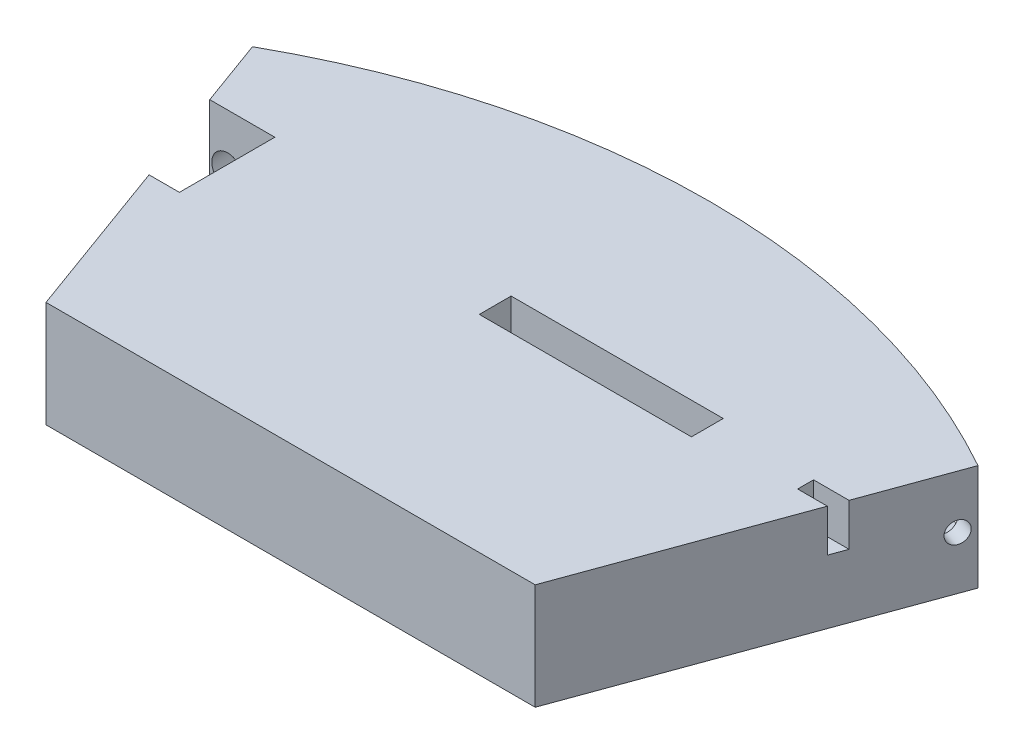
SolidWorks part; units mm, degrees
ref_plane "前视基准面" through (0, 0, 0) normal (0, 0, 1) x (1, 0, 0)
ref_plane "上视基准面" through (0, 0, 0) normal (0, 1, 0) x (1, 0, 0)
ref_plane "右视基准面" through (0, 0, 0) normal (1, 0, 0) x (0, 0, -1)
sketch "草图1" plane through (0, 0, 0) normal (0, 1, 0) x (1, 0, 0)
  line L0 (0, -1000) -> (0, 49000) construction
  line L1 (-34.202, 61.0755) -> (-9.3969, -7.0759)
  line L2 (34.202, 61.0755) -> (9.3969, -7.0759)
  circle A0 centre (0, 0) radius 70
  arc A1 (9.3969, -7.0759) -> (-9.3969, -7.0759) centre (0, -3.6557) cw
  circle A2 centre (0, 0) radius 5
  point P8 (0, -32.8937)
extrude "凸台-拉伸1" add sketch "草图1" along normal blind 48 contours A1 L0 A2 A0 L1 | L0 A1 L2 A0 A2
sketch "草图2" plane through (0, 48, 0) normal (0, 1, 0) x (1, 0, 0)
  line L0 (55.0345, 118.3122) -> (20.1256, 80.8771)
  line L1 (34.202, 61.0755) -> (9.3969, -7.0759) construction
  line L2 (36.2406, 125.1526) -> (55.0345, 118.3122)
  line L3 (36.2406, 125.1526) -> (5.4588, 40.5803)
  line L4 (5.4588, 40.5803) -> (24.2526, 33.7399)
  line L5 (55.0345, 118.3122) -> (24.2526, 33.7399)
  line L6 (36.2406, 125.1526) -> (24.2526, 33.7399) construction
  line L7 (5.4588, 40.5803) -> (55.0345, 118.3122) construction
  point P1 (30.2466, 79.4462)
  point P8 (-0.9024, -2.4793)
  dimension "D1" = 20
  dimension "D2" = 130
  dimension "D3" = 23
  dimension "D4" = 40
sketch "草图3" plane through (0, 0, 0) normal (0, 0, 1) x (1, 0, 0)
  line L0 (34.202, 48) -> (34.202, 0) construction
  line L1 (-34.202, 0) -> (-9.3969, 0) construction
  line L2 (-26.202, 8) -> (32.202, 8)
  line L3 (-26.202, 8) -> (-26.202, 2)
  line L4 (-26.202, 2) -> (32.202, 2)
  line L5 (32.202, 8) -> (32.202, 2)
  line L6 (-26.202, 8) -> (32.202, 2) construction
  line L7 (-26.202, 2) -> (32.202, 8) construction
  line L8 (-34.202, 48) -> (-34.202, 0) construction
  point P1 (3, 5)
  dimension "D1" = 2
  dimension "D2" = 8
  dimension "D3" = 6
  dimension "D4" = 2
extrude "切除-拉伸2" cut sketch "草图3" along normal blind 3 from surface starting at face at (0, 24, -65.5378)
extrude "凸台-拉伸2" add sketch "草图2" against normal blind 13
sketch "草图4" plane through (0, 0, 0) normal (1, 0, 0) x (0, 0, -1)
  line L0 (-13.6557, 48) -> (-13.6557, 0) construction
  line L1 (-13.6557, 48) -> (11.3443, 48)
  line L2 (-13.6557, 48) -> (-13.6557, 10)
  line L3 (-13.6557, 10) -> (11.3443, 10)
  line L4 (11.3443, 48) -> (11.3443, 10)
  line L5 (-13.6557, 48) -> (11.3443, 10) construction
  line L6 (-13.6557, 10) -> (11.3443, 48) construction
  line L8 (70.4669, 35) -> (30.4669, 35)
  line L9 (70.4669, 35) -> (70.4669, 10)
  line L10 (70.4669, 10) -> (30.4669, 10)
  line L11 (30.4669, 35) -> (30.4669, 10)
  line L12 (70.4669, 35) -> (30.4669, 10) construction
  line L13 (70.4669, 10) -> (30.4669, 35) construction
  line L14 (59.1533, 8) -> (67, 8) construction
  line L15 (-13.6557, 0) -> (-7.0759, 0) construction
  line L16 (118.3122, 35) -> (61.0755, 35) construction
  point P4 (-1.1557, 29)
  point P11 (50.4669, 22.5)
  dimension "D1" = 2
  dimension "D2" = 40
  dimension "D3" = 10
  dimension "D5" = 25
extrude "切除-拉伸3" cut sketch "草图4" against normal through all both and the other way through all
chamfer "倒角1" distance 5 angle 45 1 edges at (55.0345, 41.5, -118.3122)
sketch "草图6" plane through (0, 0, 0) normal (0, -1, 0) x (1, 0, 0)
  circle A0 centre (0, 0) radius 6.5
  dimension "D1" = 13
extrude "切除-拉伸4" cut sketch "草图6" against normal blind 2
sketch "草图7" plane through (0, 0, 0) normal (0, 0, 1) x (1, 0, 0)
  line L0 (-1024.202, 5) -> (48975.798, 5) construction
  line L1 (-26.202, 8) -> (-26.202, 2) construction
  line L2 (-34.202, 10) -> (-34.202, 0) construction
  circle A0 centre (-30.202, 5) radius 1.5
  point P5 (-26.202, 5)
  dimension "D1" = 3
  dimension "D2" = 4
extrude "切除-拉伸5" cut sketch "草图7" against normal blind 60
sketch "草图8" plane through (0, 10, 0) normal (0, 1, 0) x (1, 0, 0)
  line L0 (-34.202, 61.0755) -> (-16.1013, 11.3443) construction
  line L1 (-34.7582, 54.7401) -> (-25.7582, 54.7401)
  line L2 (-34.7582, 54.7401) -> (-34.7582, 45.7401)
  line L3 (-34.7582, 45.7401) -> (-25.7582, 45.7401)
  line L4 (-25.7582, 54.7401) -> (-25.7582, 45.7401)
  line L5 (-34.7582, 54.7401) -> (-25.7582, 45.7401) construction
  line L6 (-34.7582, 45.7401) -> (-25.7582, 54.7401) construction
  point P0 (-30.2582, 50.2401)
  dimension "D1" = 9
  dimension "D2" = 9
extrude "切除-拉伸6" cut sketch "草图8" against normal blind 11
sketch "草图10" plane through (10.5718, 0, 3.8478) normal (0.9397, 0, 0.342) x (0.342, 0, -0.9397)
  line L0 (-930.91, 5) -> (49069.09, 5) construction
  line L1 (69.09, 10) -> (69.09, 0) construction
  line L2 (67.59, -995) -> (67.59, 49005) construction
  circle A0 centre (67.59, 5) radius 1
  point P5 (69.09, 5)
  dimension "D1" = 2
  dimension "D2" = 1.5
extrude "切除-拉伸8" cut sketch "草图10" against normal up to surface (1.9464 mm away)
sketch "草图11" plane through (0, 0, -60) normal (0, 0, 1) x (1, 0, 0)
  circle A0 centre (-30.202, 5) radius 0.75
  dimension "D1" = 1.5
extrude "切除-拉伸9" cut sketch "草图11" against normal up to next
sketch "草图12" plane through (0, 10, 0) normal (0, 1, 0) x (1, 0, 0)
  line L1 (-1.653, 52.9115) -> (18.347, 52.9115)
  line L2 (-1.653, 52.9115) -> (-1.653, 49.9115)
  line L3 (-1.653, 49.9115) -> (18.347, 49.9115)
  line L4 (18.347, 52.9115) -> (18.347, 49.9115)
  line L5 (-1.653, 52.9115) -> (18.347, 49.9115) construction
  line L6 (-1.653, 49.9115) -> (18.347, 52.9115) construction
  point P0 (8.347, 51.4115)
  dimension "D1" = 3
  dimension "D2" = 20
  dimension "D3" = 15
extrude "切除-拉伸10" cut sketch "草图12" against normal blind 11
sketch "草图13" plane through (0, 10, 0) normal (0, 1, 0) x (1, 0, 0)
  line L0 (-976.6169, 51.4115) -> (49023.3831, 51.4115) construction
  line L1 (18.347, 49.9115) -> (18.347, 52.9115) construction
  line L3 (27.6086, 52.1615) -> (31.4769, 52.1615)
  line L4 (27.6086, 52.1615) -> (27.6086, 50.6615)
  line L5 (27.6086, 50.6615) -> (31.4769, 50.6615)
  line L6 (31.4769, 52.1615) -> (31.4769, 50.6615)
  line L7 (27.6086, 52.1615) -> (31.4769, 50.6615) construction
  line L8 (27.6086, 50.6615) -> (31.4769, 52.1615) construction
  point P4 (18.347, 51.4115)
  point P5 (29.5428, 51.4115)
  dimension "D1" = 1.5
extrude "切除-拉伸11" cut sketch "草图13" against normal blind 4
sketch "草图14" plane through (0, 48, 0) normal (0, 1, 0) x (1, 0, 0)
  line L0 (51.6245, 114.6554) -> (20.1256, 80.8771) construction
  line L1 (49.7661, 108.2233) -> (49.0348, 108.9053)
  line L2 (49.7661, 108.2233) -> (40.9002, 98.7157)
  line L3 (40.9002, 98.7157) -> (40.1688, 99.3977)
  line L4 (49.0348, 108.9053) -> (40.1688, 99.3977)
  line L5 (49.7661, 108.2233) -> (40.1688, 99.3977) construction
  line L6 (40.9002, 98.7157) -> (49.0348, 108.9053) construction
  line L9 (53.7303, 114.729) -> (16.1013, 11.3443) construction
  point P4 (44.9675, 103.8105)
  dimension "D1" = 1
  dimension "D2" = 13
  dimension "D3" = 13
  dimension "D4" = 1
  dimension "D5" = 90
  dimension "D6" = 4.5
  dimension "D7" = 14
extrude "切除-拉伸12" cut sketch "草图14" against normal up to next
sketch "草图15" plane through (0, 10, 0) normal (0, 1, 0) x (1, 0, 0)
  line L0 (-941.071, 30.4669) -> (49058.929, 30.4669) construction
  line L1 (-51.0427, 30.4669) -> (58.929, 30.4669)
  line L2 (-51.0427, 30.4669) -> (-51.0427, 79.7213)
  line L3 (-51.0427, 79.7213) -> (58.929, 79.7213)
  line L4 (58.929, 30.4669) -> (58.929, 79.7213)
  line L5 (-51.0427, 30.4669) -> (58.929, 79.7213) construction
  line L6 (-51.0427, 79.7213) -> (58.929, 30.4669) construction
  line L7 (-23.0614, 30.4669) -> (23.0614, 30.4669) construction
  point P4 (3.9431, 55.0941)
  point P6 (0, 0)
  point P9 (-51.0427, 33.611)
extrude "切除-拉伸13" cut sketch "草图15" against normal blind 10 flip side to cut
